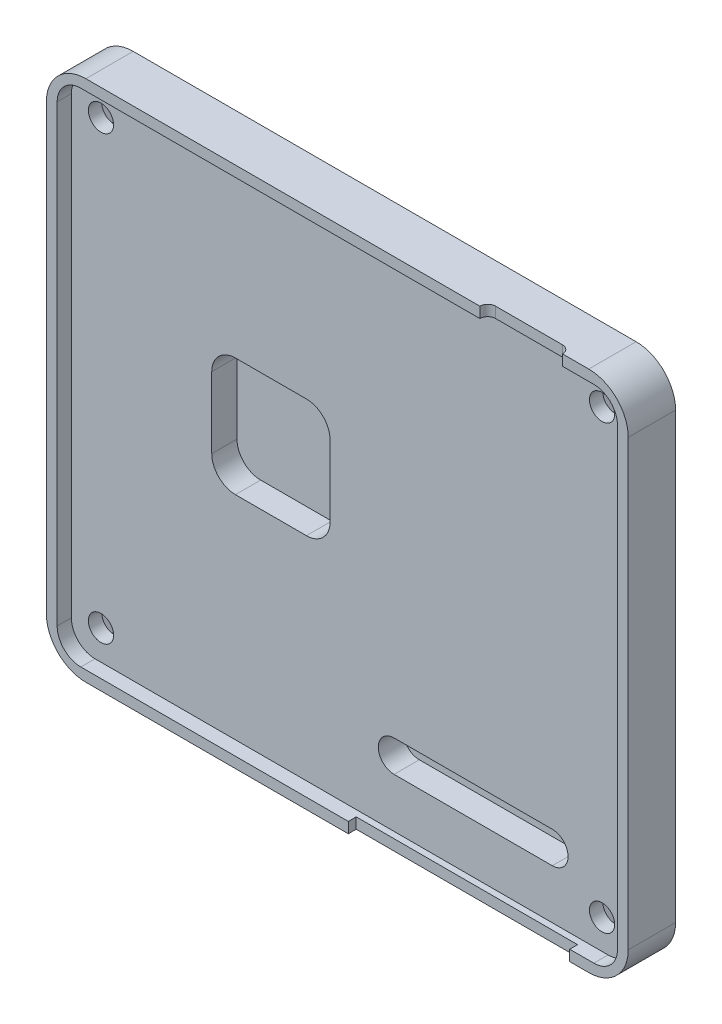
SolidWorks part; units mm, degrees
ref_plane "前视基准面" through (0, 0, 0) normal (0, 0, 1) x (1, 0, 0)
ref_plane "上视基准面" through (0, 0, 0) normal (0, 1, 0) x (1, 0, 0)
ref_plane "右视基准面" through (0, 0, 0) normal (1, 0, 0) x (0, 0, -1)
sketch "草图1" plane through (0, 0, 0) normal (0, 0, 1) x (1, 0, 0)
  line L1 (0, 0) -> (73.73, 0)
  line L2 (0, 0) -> (0, 66.24)
  line L3 (0, 66.24) -> (73.73, 66.24)
  line L4 (73.73, 0) -> (73.73, 66.24)
  dimension "D1" = 73.73
  dimension "D2" = 66.24
extrude "凸台-拉伸1" add sketch "草图1" along normal blind 6
sketch "草图2" plane through (0, 0, 6) normal (0, 0, 1) x (1, 0, 0)
  line L2 (1.761, 61.0603) -> (1.7634, 61.0603)
  line L5 (36.865, 66.24) -> (36.865, 0) construction
  line L6 (73.73, 66.24) -> (0, 66.24) construction
  line L7 (0, 0) -> (73.73, 0) construction
  line L8 (73.73, 33.12) -> (0, 33.12) construction
  line L9 (73.73, 0) -> (73.73, 66.24) construction
  line L10 (0, 66.24) -> (0, 0) construction
  line L12 (4.36, 1.36) -> (69.37, 1.36)
  line L13 (1.36, 4.36) -> (1.36, 61.88)
  line L14 (4.36, 64.88) -> (69.37, 64.88)
  line L15 (72.37, 4.36) -> (72.37, 61.88)
  arc A22 (1.36, 61.88) -> (4.36, 64.88) centre (4.36, 61.88) cw
  arc A23 (4.36, 1.36) -> (1.36, 4.36) centre (4.36, 4.36) cw
  arc A24 (69.37, 1.36) -> (72.37, 4.36) centre (69.37, 4.36) ccw
  arc A25 (69.37, 64.88) -> (72.37, 61.88) centre (69.37, 61.88) cw
  point P0 (0, 0)
  point P1 (0, 0)
  dimension "D2" = 1.36
  dimension "D11" = 3
  dimension "D3" = 1.36
extrude "切除-拉伸1" cut sketch "草图2" against normal blind 1.8
sketch "草图5" plane through (0, 0, 4.2) normal (0, 0, 1) x (1, 0, 0)
  line L0 (36.865, 64.88) -> (36.865, 1.36) construction
  line L3 (1.36, 33.12) -> (72.37, 33.12) construction
  line L11 (1.36, 4.36) -> (1.36, 61.88) construction
  line L12 (72.37, 4.36) -> (72.37, 61.88) construction
  line L13 (4.36, 1.36) -> (69.37, 1.36) construction
  line L14 (4.36, 64.88) -> (69.37, 64.88) construction
  circle A0 centre (5.115, 61.125) radius 1.6
  circle A1 centre (68.615, 61.125) radius 1.6
  circle A2 centre (68.615, 5.115) radius 1.6
  circle A3 centre (5.115, 5.115) radius 1.6
  point P2 (0, 0)
  point P3 (0, 0)
  point P4 (0, 0)
  point P5 (0, 0)
  point P10 (0, 0)
  point P11 (0, 0)
  point P20 (0, 0)
  point P21 (0, 0)
  point P22 (0, 0)
  point P23 (0, 0)
  point P24 (0, 0)
  point P27 (0, 0)
  point P28 (0, 0)
  point P31 (0, 0)
  dimension "D1" = 3.2
  dimension "D2" = 63.5
  dimension "D3" = 56.01
extrude "切除-拉伸2" cut sketch "草图5" against normal through all
sketch "草图6" plane through (0, 0, 4.2) normal (0, 0, 1) x (1, 0, 0)
  line L0 (62.308, 9.6211) -> (42.257, 9.6211) construction
  line L1 (62.308, 7.6211) -> (42.257, 7.6211)
  line L2 (62.308, 11.6211) -> (42.257, 11.6211)
  line L3 (4.36, 1.36) -> (69.37, 1.36) construction
  line L4 (72.37, 4.36) -> (72.37, 61.88) construction
  line L5 (26.6512, 32.2616) -> (26.6509, 39.272) construction
  line L6 (23.146, 32.2615) -> (30.1564, 32.2618) construction
  line L7 (30.1561, 39.2722) -> (23.1457, 39.2719) construction
  line L8 (30.1562, 35.767) -> (23.1458, 35.7667) construction
  line L9 (30.1564, 32.2618) -> (30.1561, 39.2722) construction
  line L10 (23.1457, 39.2719) -> (23.146, 32.2615) construction
  line L12 (31.151, 43.2668) -> (22.151, 43.2668)
  line L13 (34.151, 40.2668) -> (34.151, 31.2668)
  line L14 (31.151, 28.2668) -> (22.151, 28.2668)
  line L15 (19.151, 40.2668) -> (19.151, 31.2668)
  line L16 (34.151, 43.2668) -> (19.151, 28.2668) construction
  line L17 (34.151, 28.2668) -> (19.151, 43.2668) construction
  arc A0 (62.308, 7.6211) -> (62.308, 11.6211) centre (62.308, 9.6211) ccw
  arc A1 (42.257, 11.6211) -> (42.257, 7.6211) centre (42.257, 9.6211) ccw
  arc A2 (22.151, 43.2668) -> (19.151, 40.2668) centre (22.151, 40.2668) ccw
  arc A3 (31.151, 43.2668) -> (34.151, 40.2668) centre (31.151, 40.2668) cw
  arc A4 (22.151, 28.2668) -> (19.151, 31.2668) centre (22.151, 31.2668) cw
  arc A5 (34.151, 31.2668) -> (31.151, 28.2668) centre (31.151, 31.2668) cw
  point P2 (52.2825, 9.6211)
  point P23 (26.651, 35.7668)
  dimension "D1" = 2
  dimension "D6" = 3
  dimension "D2" = 20.051
  dimension "D3" = 8.2611
  dimension "D4" = 10.062
  dimension "D5" = 15
extrude "切除-拉伸3" cut sketch "草图6" against normal blind 3.2
sketch "草图10" plane through (0, 66.24, 0) normal (0, 1, 0) x (1, 0, 0)
  line L0 (60.1618, -9.0184) -> (60.1618, -5.8784) construction
  line L1 (63.6318, -9.0184) -> (56.6918, -9.0184) construction
  line L2 (56.6918, -5.8784) -> (63.6318, -5.8784) construction
  line L3 (55.9218, -5) -> (64.4018, -5)
  line L4 (55.9218, -10.0184) -> (64.4018, -10.0184) construction
  line L5 (55.9218, -5) -> (55.9218, -6) construction
  line L7 (73.73, -6) -> (0, -6) construction
  line L8 (5, -6) -> (54.9218, -6) construction
  line L9 (54.9218, -6) -> (65.4018, -6)
  arc A0 (55.9218, -5) -> (54.9218, -6) centre (55.9218, -6) ccw
  arc A1 (64.4018, -5) -> (65.4018, -6) centre (64.4018, -6) cw
  dimension "D2" = 1
extrude "切除-拉伸7" cut sketch "草图10" against normal blind 9
sketch "草图11" plane through (0, 0, 0) normal (0, -1, 0) x (1, 0, 0)
  line L0 (66.3081, 6) -> (66.3081, 12.5284) construction
  line L1 (38.2572, 6) -> (66.3081, 6)
  line L2 (38.2572, 6) -> (38.2572, 5)
  line L3 (38.2572, 5) -> (66.3081, 5)
  line L4 (66.3081, 6) -> (66.3081, 5)
  dimension "D1" = 1
extrude "切除-拉伸8" cut sketch "草图11" against normal blind 9
fillet "圆角1" radius 5 4 edges at (73.73, 66.24, 3) (73.73, 0, 3) (0, 66.24, 3) (0, 0, 3)
sketch "草图12" plane through (0, 0, 0) normal (0, 0, -1) x (-1, 0, 0)
  line L0 (-68.73, 66.24) -> (-5, 66.24) construction
  line L1 (-65.1509, 61.125) -> (-66.8829, 64.125)
  line L2 (-66.8829, 64.125) -> (-70.3471, 64.125)
  line L3 (-70.3471, 64.125) -> (-72.0791, 61.125)
  line L4 (-72.0791, 61.125) -> (-70.3471, 58.125)
  line L5 (-70.3471, 58.125) -> (-66.8829, 58.125)
  line L6 (-66.8829, 58.125) -> (-65.1509, 61.125)
  line L7 (-65.1509, 5.115) -> (-66.8829, 8.115)
  line L8 (-66.8829, 8.115) -> (-70.3471, 8.115)
  line L9 (-70.3471, 8.115) -> (-72.0791, 5.115)
  line L10 (-72.0791, 5.115) -> (-70.3471, 2.115)
  line L11 (-70.3471, 2.115) -> (-66.8829, 2.115)
  line L12 (-66.8829, 2.115) -> (-65.1509, 5.115)
  line L13 (-1.6509, 5.115) -> (-3.3829, 8.115)
  line L14 (-3.3829, 8.115) -> (-6.8471, 8.115)
  line L15 (-6.8471, 8.115) -> (-8.5791, 5.115)
  line L16 (-8.5791, 5.115) -> (-6.8471, 2.115)
  line L17 (-6.8471, 2.115) -> (-3.3829, 2.115)
  line L18 (-3.3829, 2.115) -> (-1.6509, 5.115)
  line L19 (-1.6509, 61.125) -> (-3.3829, 64.125)
  line L20 (-3.3829, 64.125) -> (-6.8471, 64.125)
  line L21 (-6.8471, 64.125) -> (-8.5791, 61.125)
  line L22 (-8.5791, 61.125) -> (-6.8471, 58.125)
  line L23 (-6.8471, 58.125) -> (-3.3829, 58.125)
  line L24 (-3.3829, 58.125) -> (-1.6509, 61.125)
  circle A0 centre (-68.615, 61.125) radius 3 construction
  circle A1 centre (-68.615, 5.115) radius 3 construction
  circle A2 centre (-5.115, 5.115) radius 3 construction
  circle A3 centre (-5.115, 61.125) radius 3 construction
  dimension "D1" = 6
extrude "切除-拉伸9" cut sketch "草图12" against normal blind 2.5
